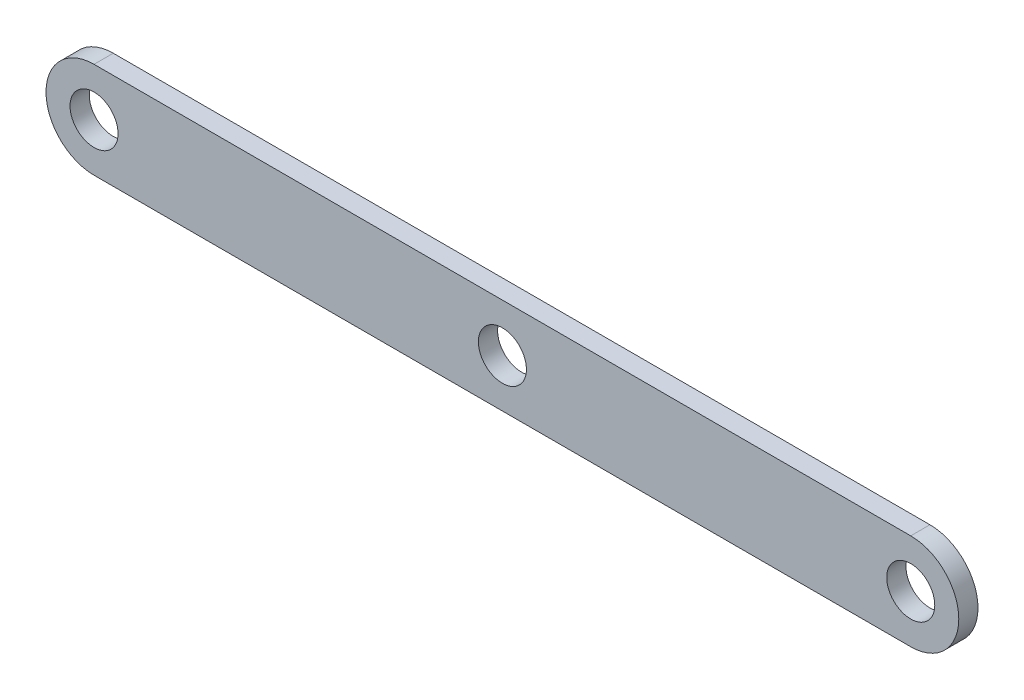
SolidWorks part; units mm, degrees
ref_plane "前视基准面" through (0, 0, 0) normal (0, 0, 1) x (1, 0, 0)
ref_plane "上视基准面" through (0, 0, 0) normal (0, 1, 0) x (1, 0, 0)
ref_plane "右视基准面" through (0, 0, 0) normal (1, 0, 0) x (0, 0, -1)
sketch "草图1" plane through (0, 0, 0) normal (0, 0, 1) x (1, 0, 0)
  line L1 (-42.5, -5) -> (42.5, -5)
  line L2 (-42.5, -5) -> (-42.5, 5) construction
  line L3 (-42.5, 5) -> (42.5, 5)
  line L4 (42.5, -5) -> (42.5, 5) construction
  line L5 (-42.5, -5) -> (42.5, 5) construction
  line L6 (-42.5, 5) -> (42.5, -5) construction
  arc A0 (-42.5, 5) -> (-42.5, -5) centre (-42.5, 0) ccw
  circle A1 centre (-42.5, 0) radius 2.5
  circle A2 centre (42.5, 0) radius 2.5
  circle A3 centre (0, 0) radius 2.5
  arc A4 (42.5, -5) -> (42.5, 5) centre (42.5, 0) ccw
  point P0 (0, 0)
  dimension "D3" = 5
  dimension "D4" = 5
  dimension "D5" = 5
  dimension "D1" = 85
  dimension "D2" = 10
extrude "凸台-拉伸1" add sketch "草图1" along normal blind 2
